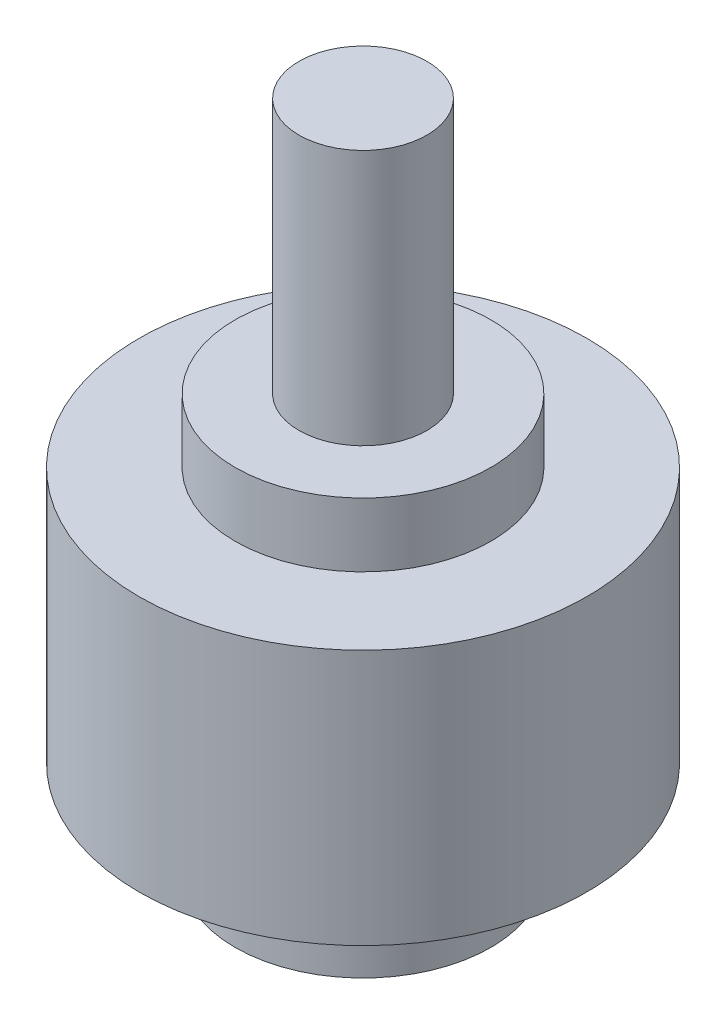
SolidWorks part; units mm, degrees
material "PW50:3:Ar:0:-1:C1:1:2:3:Re:11:"
ref_plane "front" through (0, 0, 0) normal (0, 0, 1) x (1, 0, 0)
ref_plane "top" through (0, 0, 0) normal (0, 1, 0) x (1, 0, 0)
ref_plane "side" through (0, 0, 0) normal (1, 0, 0) x (0, 0, -1)
sketch "Sketch1" plane through (0, 0, 0) normal (0, 0, 1) x (1, 0, 0)
  line L0 (0, 0) -> (0, -28.7465) construction
  line L1 (0, 0) -> (25.4, 0)
  line L2 (25.4, 0) -> (25.4, 19.05)
  line L3 (25.4, 19.05) -> (44.45, 19.05)
  line L4 (44.45, 19.05) -> (44.45, 69.85)
  line L5 (44.45, 69.85) -> (25.4, 69.85)
  line L6 (25.4, 69.85) -> (25.4, 82.55)
  line L7 (25.4, 82.55) -> (12.7, 82.55)
  line L8 (12.7, 82.55) -> (12.7, 133.35)
  line L9 (12.7, 133.35) -> (0, 133.35)
  line L10 (0, 133.35) -> (0, 0)
  dimension "D1" = 50.8
  dimension "D2" = 19.05
  dimension "D3" = 50.8
  dimension "D4" = 12.7
  dimension "D5" = 25.4
  dimension "D6" = 50.8
  dimension "D7" = 88.9
revolve "Base-Revolve" add sketch "Sketch1" angle 360 about L0
sketch "Sketch2" plane through (0, 0, 0) normal (0, -1, 0) x (1, 0, 0)
  circle A0 centre (0, 0) radius 12.7
  dimension "D1" = 25.4
extrude "Cut-Extrude1" cut sketch "Sketch2" against normal blind 50.8
